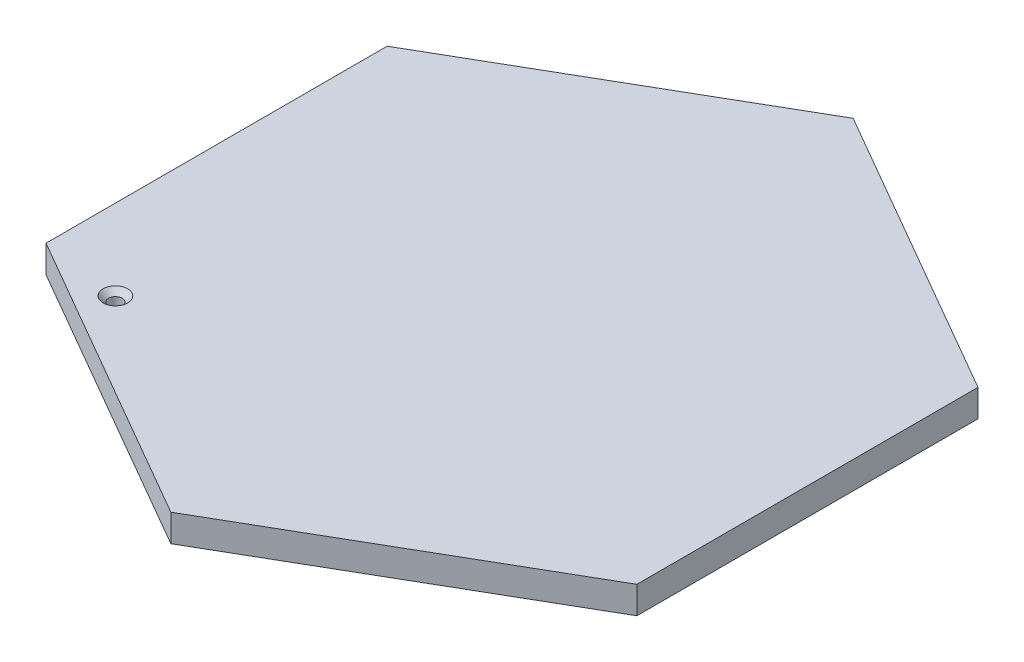
SolidWorks part; units mm, degrees
ref_plane "Front Plane" through (0, 0, 0) normal (0, 0, 1) x (1, 0, 0)
ref_plane "Top Plane" through (0, 0, 0) normal (0, 1, 0) x (1, 0, 0)
ref_plane "Right Plane" through (0, 0, 0) normal (1, 0, 0) x (0, 0, -1)
sketch "Sketch1" plane through (0, 0, 0) normal (0, 1, 0) x (1, 0, 0)
  line L1 (0, 50) -> (-43.3013, 25)
  line L2 (-43.3013, 25) -> (-43.3013, -25)
  line L3 (-43.3013, -25) -> (0, -50)
  line L4 (0, -50) -> (43.3013, -25)
  line L5 (43.3013, -25) -> (43.3013, 25)
  line L6 (43.3013, 25) -> (0, 50)
  circle A0 centre (0, 0) radius 43.3013 construction
  dimension "D1" = 100
extrude "Boss-Extrude1" add sketch "Sketch1" along normal blind 4
hole_wizard "CSK for M1.6 Countersunk Flat Head Screw1" positions "Sketch2" profile "Sketch3" countersink size "M1.6" standard "ISO" end condition through all
sketch "Sketch2" plane through (-40.5678, 4, -91.8333) normal (0, 1, 0) x (1, 0, 0)
  point P0 (9.0428, -118.4362)
sketch "Sketch3" plane through (-31.525, 4, 26.6029) normal (1, 0, 0) x (0, 0, 1)
  line L0 (0, 0) -> (0, 4)
  line L1 (0, 4) -> (1, 4)
  line L2 (1, 4) -> (1, 0.8)
  line L3 (1, 0.8) -> (1.8, 0)
  line L4 (1.8, 0) -> (0, 0)
  line L5 (-1, 0.8) -> (-1.8, 0) construction
  line L6 (0, -6.35) -> (0, 107.95) construction
  dimension "Thru Hole Dia." = 2
  dimension "Thru Hole Depth" = 4
  dimension "Near C'Sink Dia." = 3.6
  dimension "Near C'Sink Angle" = 90
